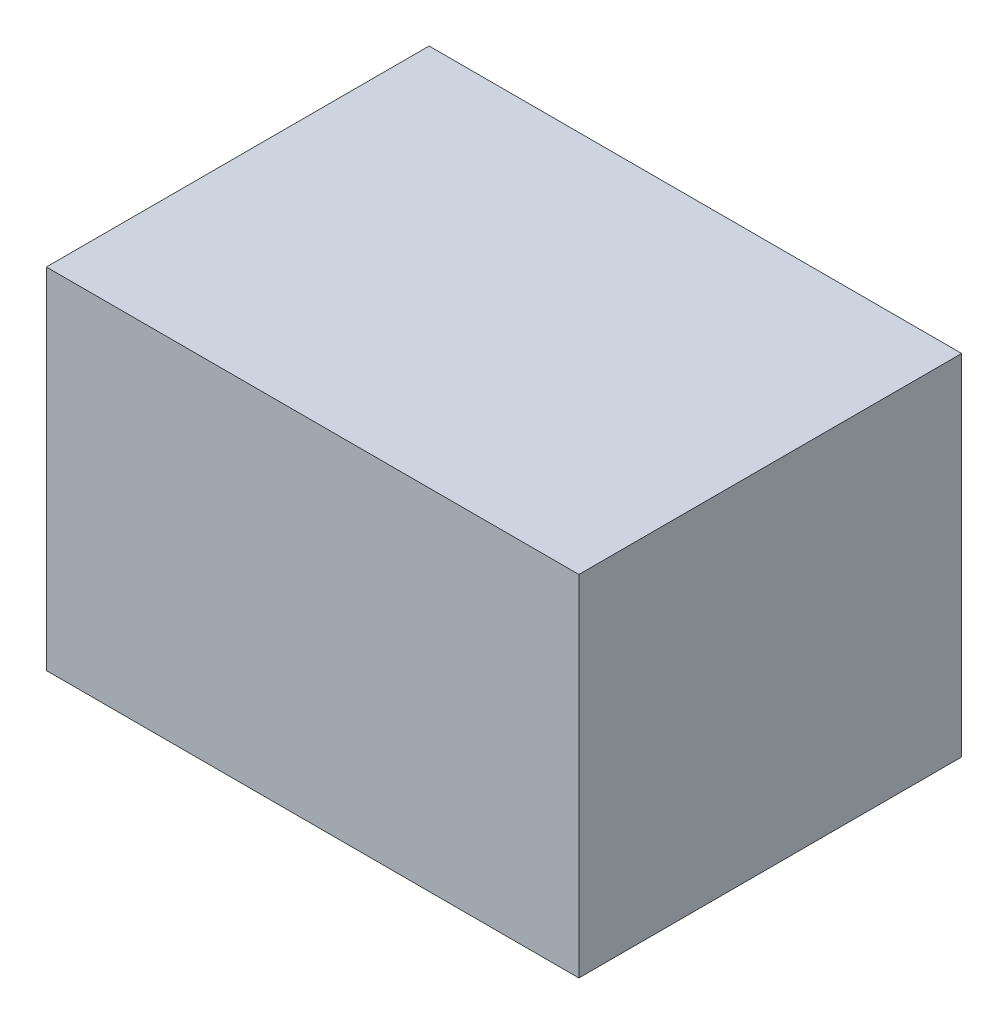
SolidWorks part; units mm, degrees
material "Acrylic (Medium-high impact)"
ref_plane "Front Plane" through (0, 0, 0) normal (0, 0, 1) x (1, 0, 0)
ref_plane "Top Plane" through (0, 0, 0) normal (0, 1, 0) x (1, 0, 0)
ref_plane "Right Plane" through (0, 0, 0) normal (1, 0, 0) x (0, 0, -1)
sketch "Sketch1" plane through (0, 0, 0) normal (0, 1, 0) x (1, 0, 0)
  line L1 (-160, -115) -> (160, -115)
  line L2 (-160, -115) -> (-160, 115)
  line L3 (-160, 115) -> (160, 115)
  line L4 (160, -115) -> (160, 115)
  line L5 (-160, -115) -> (160, 115) construction
  line L6 (-160, 115) -> (160, -115) construction
  point P0 (0, 0)
  dimension "D1" = 320
  dimension "D2" = 230
extrude "Boss-Extrude1" add sketch "Sketch1" along normal blind 210
shell "Shell1" thickness 10
